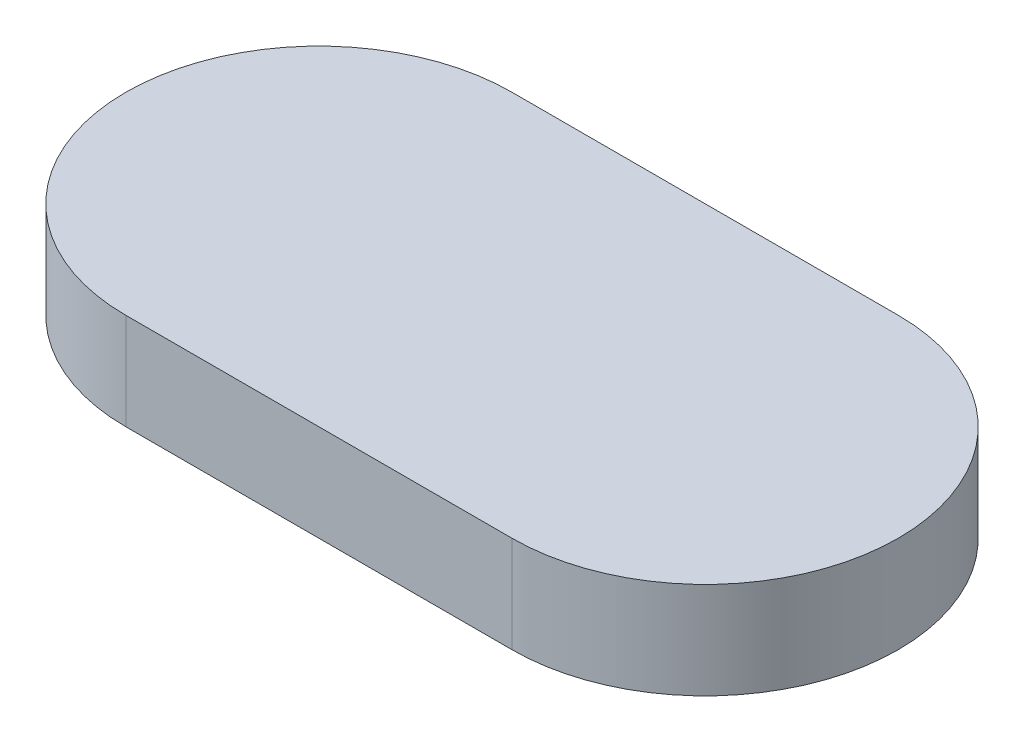
SolidWorks part; units mm, degrees
ref_plane "前视基准面" through (0, 0, 0) normal (0, 0, 1) x (1, 0, 0)
ref_plane "上视基准面" through (0, 0, 0) normal (0, 1, 0) x (1, 0, 0)
ref_plane "右视基准面" through (0, 0, 0) normal (1, 0, 0) x (0, 0, -1)
sketch "草图1" plane through (0, 0, 0) normal (0, 1, 0) x (1, 0, 0)
  line L0 (0, 0) -> (-40, 0) construction
  line L1 (0, -20) -> (-40, -20)
  line L2 (0, 20) -> (-40, 20)
  arc A0 (0, -20) -> (0, 20) centre (0, 0) ccw
  arc A1 (-40, 20) -> (-40, -20) centre (-40, 0) ccw
  point P3 (-20, 0)
  dimension "D1" = 20
  dimension "D2" = 40
extrude "凸台-拉伸1" add sketch "草图1" along normal blind 10
